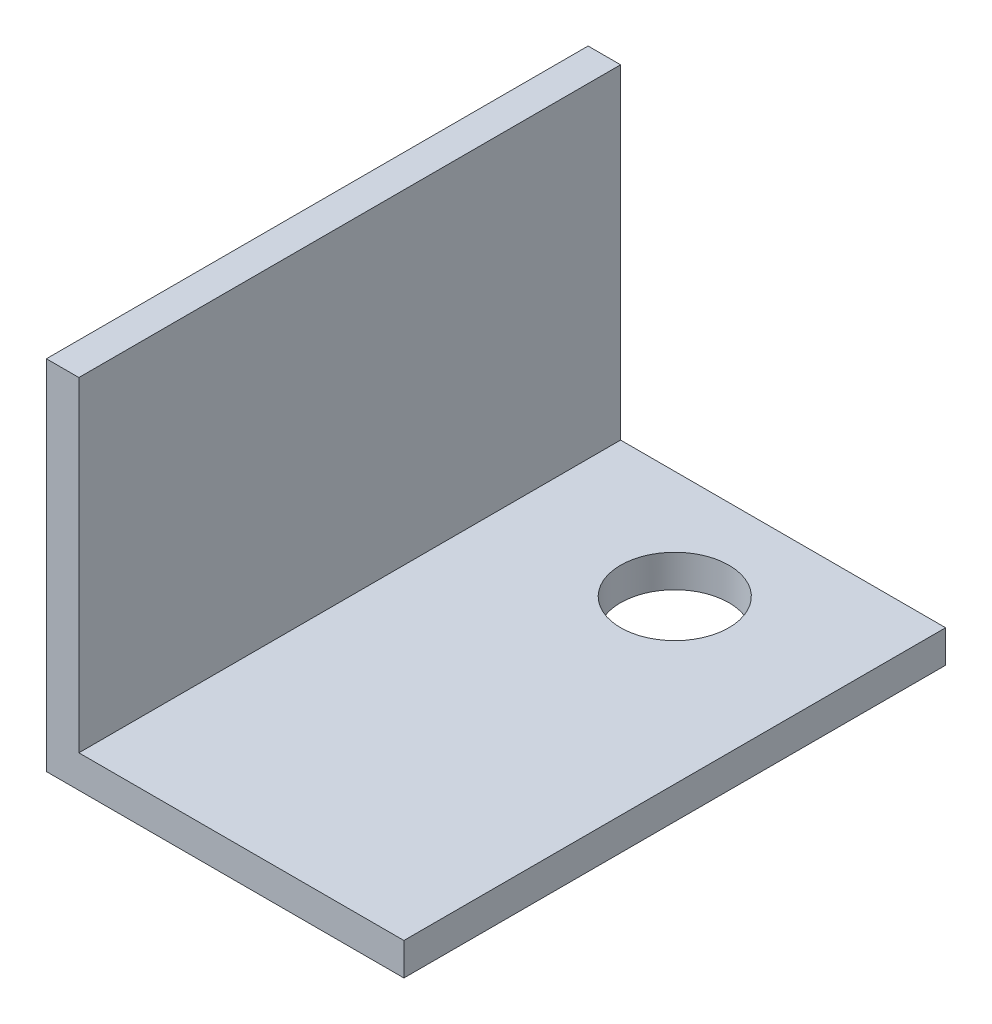
SolidWorks part; units mm, degrees
ref_plane "Спереди" through (0, 0, 0) normal (0, 0, 1) x (1, 0, 0)
ref_plane "Сверху" through (0, 0, 0) normal (0, 1, 0) x (1, 0, 0)
ref_plane "Справа" through (0, 0, 0) normal (1, 0, 0) x (0, 0, -1)
sketch "Эскиз1" plane through (0, 0, 0) normal (0, 0, 1) x (1, 0, 0)
  line L0 (0, 30) -> (0, 0)
  line L1 (0, 0) -> (30, 0)
extrude "Вытянуть-Тонкостенный1" add sketch "Эскиз1" against normal blind 50 thin
sketch "Эскиз2" plane through (0, -3, 0) normal (0, 1, 0) x (0, 0, 1)
  circle A0 centre (-40, 15) radius 5
extrude "Вырез-Вытянуть1" cut sketch "Эскиз2" along normal blind 10
